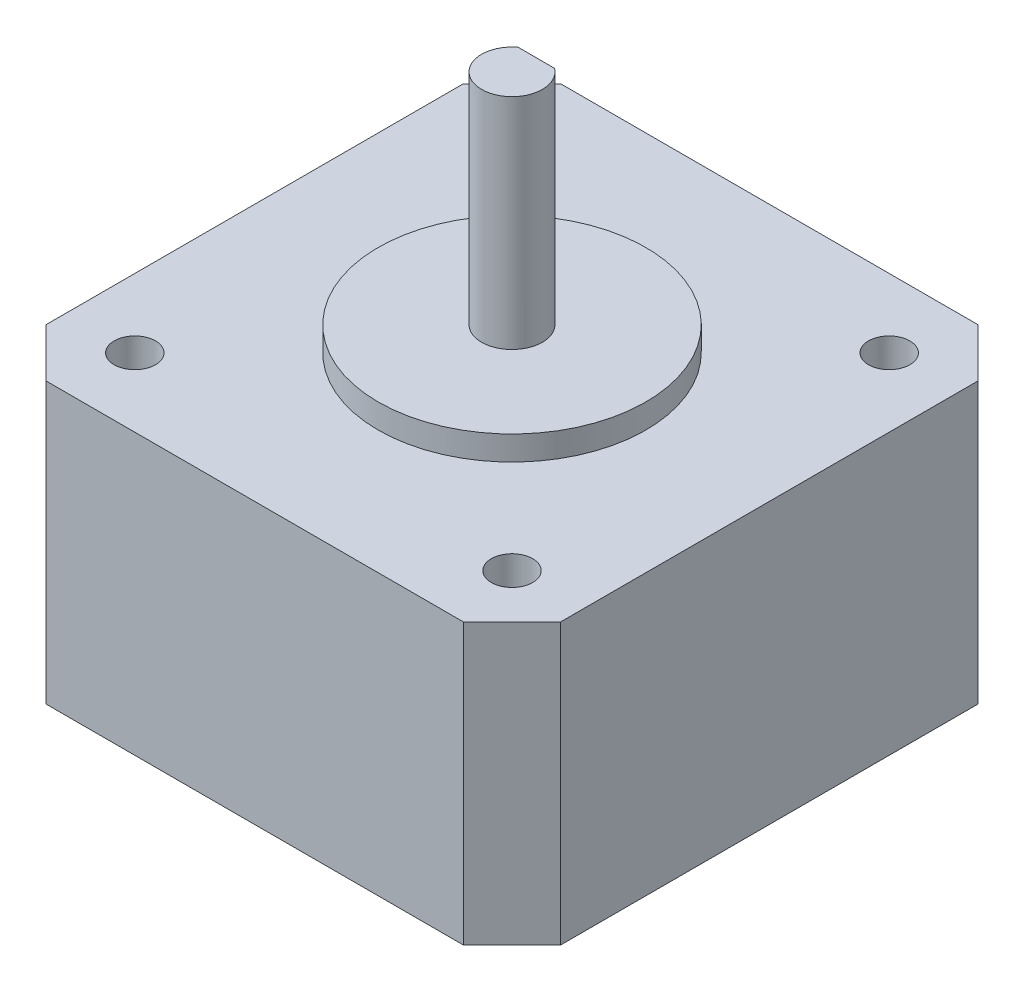
SolidWorks part; units mm, degrees
ref_plane "Piano frontale" through (0, 0, 0) normal (0, 0, 1) x (1, 0, 0)
ref_plane "Piano superiore" through (0, 0, 0) normal (0, 1, 0) x (1, 0, 0)
ref_plane "Piano destro" through (0, 0, 0) normal (1, 0, 0) x (0, 0, -1)
sketch "Schizzo1" plane through (0, 0, 0) normal (0, 1, 0) x (1, 0, 0)
  line L0 (21.15, -17.15) -> (21.15, 17.15)
  line L1 (21.15, 17.15) -> (17.15, 21.15)
  line L2 (17.15, 21.15) -> (-17.15, 21.15)
  line L3 (-17.15, 21.15) -> (-21.15, 17.15)
  line L4 (-21.15, 17.15) -> (-21.15, -17.15)
  line L5 (-21.15, -17.15) -> (-17.15, -21.15)
  line L6 (-17.15, -21.15) -> (17.15, -21.15)
  line L7 (17.15, -21.15) -> (21.15, -17.15)
  line L8 (-19.15, -19.15) -> (19.15, 19.15) construction
  line L9 (19.15, -19.15) -> (-19.15, 19.15) construction
  line L10 (-15.5, -15.5) -> (-15.5, 15.5) construction
  line L11 (0, -21.15) -> (0, 21.15) construction
  line L12 (-15.5, 15.5) -> (15.5, 15.5) construction
  line L13 (15.5, 15.5) -> (15.5, -15.5) construction
  line L14 (15.5, -15.5) -> (-15.5, -15.5) construction
  line L15 (-17.15, 21.15) -> (-17.15, -21.15) construction
  circle A4 centre (-15.5, 15.5) radius 1.65 construction
  circle A5 centre (15.5, 15.5) radius 1.65 construction
  circle A6 centre (15.5, -15.5) radius 1.65 construction
  circle A7 centre (-15.5, -15.5) radius 1.65 construction
  point P12 (0, 0)
  dimension "D3" = 3.3
  dimension "D4" = 31
  dimension "D1" = 42.3
  dimension "D2" = 42.3
extrude "Estrusione-Estrusione1" add sketch "Schizzo1" along normal blind 23
sketch "Schizzo3" plane through (0, 0, 0) normal (0, -1, 0) x (-1, 0, 0)
  line L0 (-15.5, -15.5) -> (-15.5, 15.5) construction
  line L1 (-15.5, 15.5) -> (15.5, 15.5) construction
  line L2 (15.5, 15.5) -> (15.5, -15.5) construction
  line L3 (15.5, -15.5) -> (-15.5, -15.5) construction
  line L5 (-19.15, -19.15) -> (19.15, 19.15) construction
  line L6 (-17.15, -21.15) -> (-21.15, -17.15) construction
  line L7 (17.15, 21.15) -> (21.15, 17.15) construction
  line L9 (19.15, -19.15) -> (-19.15, 19.15) construction
  line L10 (21.15, -17.15) -> (17.15, -21.15) construction
  line L11 (-21.15, 17.15) -> (-17.15, 21.15) construction
  point P0 (-15.5, 15.5)
  point P2 (15.5, 15.5)
  point P4 (15.5, -15.5)
  point P6 (-15.5, -15.5)
  dimension "D1" = 31
hole_wizard "Foro per Vite M3-1" positions "Schizzo3" profile "Schizzo4" hole size "M3" standard "ISO"
sketch "Schizzo4" plane through (15.5, 0, -15.5) normal (1, 0, 0) x (0, 0, -1)
  line L0 (0, 0) -> (0, 35.0215)
  line L1 (0, 35.0215) -> (1.7, 34)
  line L2 (1.7, 34) -> (1.7, 0.025)
  line L3 (1.7, 0.025) -> (1.725, 0)
  line L5 (1.725, 0) -> (0, 0)
  line L6 (-1.7, 0.025) -> (-1.725, 0) construction
  line L10 (0, 35.0215) -> (-1.7, 34) construction
  line L11 (0, -6.35) -> (0, 107.95) construction
  dimension "Hole Dia." = 3.4
  dimension "Hole Depth" = 34
  dimension "Near C'Sink Dia." = 3.45
  dimension "Near C'Sink Angle" = 90
  dimension "Drill Angle" = 118
sketch "Schizzo5" plane through (0, 23, 0) normal (0, 1, 0) x (1, 0, 0)
  circle A0 centre (0, 0) radius 11
  dimension "D1" = 22
extrude "Estrusione-Estrusione2" add sketch "Schizzo5" along normal blind 2
sketch "Schizzo6" plane through (0, 25, 0) normal (0, 1, 0) x (1, 0, 0)
  circle A0 centre (0, 0) radius 2.5
  dimension "D1" = 5
extrude "Estrusione-Estrusione3" add sketch "Schizzo6" along normal blind 18
sketch "Schizzo7" plane through (0, 43, 0) normal (0, 1, 0) x (1, 0, 0)
  line L0 (-1.5, 2) -> (1.5, 2)
  circle A0 centre (0, 0) radius 2.5 construction
  arc A2 (1.5, 2) -> (-1.5, 2) centre (0, 0) ccw
  dimension "D1" = 2
extrude "Taglio-Estrusione1" cut sketch "Schizzo7" against normal blind 17
